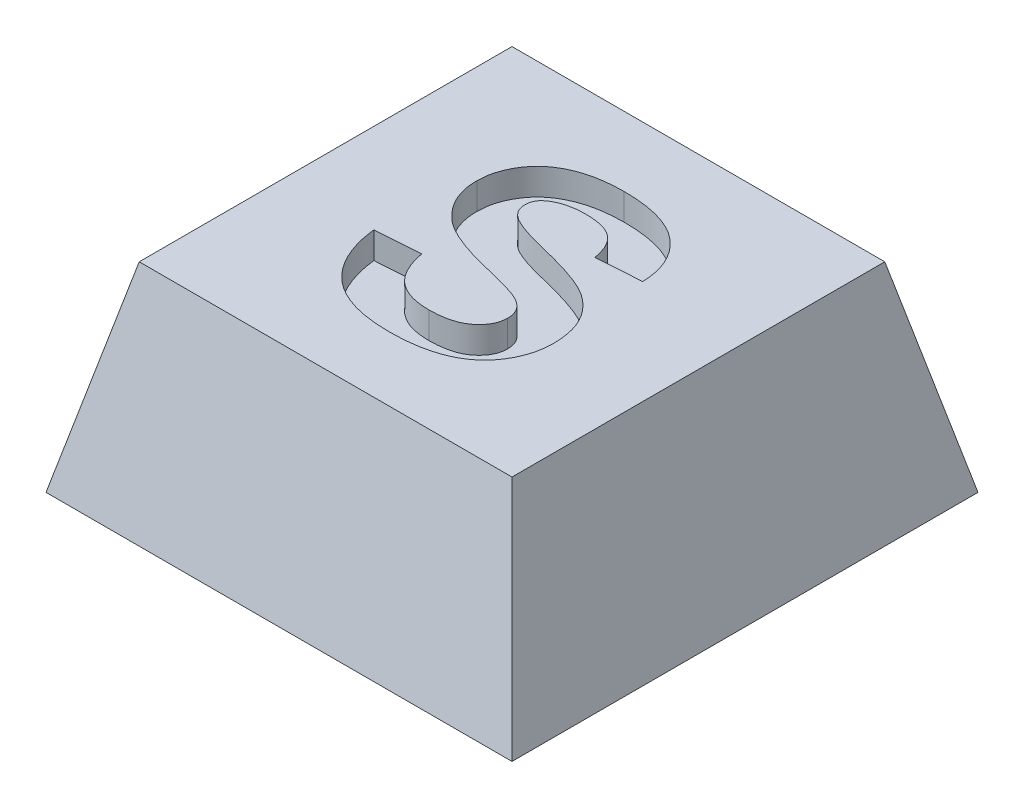
SolidWorks part; units mm, degrees
ref_plane "Front Plane" through (0, 0, 0) normal (0, 0, 1) x (1, 0, 0)
ref_plane "Top Plane" through (0, 0, 0) normal (0, 1, 0) x (1, 0, 0)
ref_plane "Right Plane" through (0, 0, 0) normal (1, 0, 0) x (0, 0, -1)
sketch "Sketch1" plane through (0, 0, 0) normal (0, 1, 0) x (1, 0, 0)
  line L1 (0, 0) -> (7, 0)
  line L2 (0, 0) -> (0, 7)
  line L3 (0, 7) -> (7, 7)
  line L4 (7, 0) -> (7, 7)
  dimension "D1" = 7
  dimension "D2" = 7
extrude "Boss-Extrude1" add sketch "Sketch1" along normal blind 3
sketch "Sketch2" plane through (0, 0, 0) normal (0, 0, 1) x (1, 0, 0)
  line L0 (0, 0) -> (0.7, 3)
  line L1 (0, 3) -> (7, 3) construction
  line L2 (0.7, 3) -> (0, 3)
  line L3 (0, 3) -> (0, 0)
  line L4 (7, 0) -> (6.3, 3)
  line L5 (6.3, 3) -> (7, 3)
  line L6 (7, 3) -> (7, 0)
  dimension "D1" = 0.7
  dimension "D2" = 0.7
extrude "Cut-Extrude1" cut sketch "Sketch2" against normal blind 7
sketch "Sketch3" plane through (0, 0, 0) normal (1, 0, 0) x (0, 0, -1)
  line L0 (0, 0) -> (0.7, 3)
  line L1 (7, 3) -> (0, 3) construction
  line L2 (0.7, 3) -> (0, 3)
  line L3 (0, 3) -> (0, 0)
  line L4 (7, 3) -> (6.3, 3)
  line L5 (6.3, 3) -> (7, 0)
  line L6 (7, 3) -> (7, 0)
  dimension "D1" = 0.7
  dimension "D2" = 0.7
extrude "Cut-Extrude2" cut sketch "Sketch3" along normal blind 11
sketch "Sketch4" plane through (0, 0, 0) normal (0, -1, 0) x (1, 0, 0)
  line L0 (3.5, 0) -> (3.5, -7) construction
  line L1 (0, 0) -> (7, 0) construction
  line L2 (7, -7) -> (0, -7) construction
  line L3 (0, -3.5) -> (7, -3.5) construction
  line L4 (0, -7) -> (0, 0) construction
  line L5 (7, 0) -> (7, -7) construction
  circle A0 centre (3.5, -3.5) radius 1.8
  dimension "D1" = 3.6
extrude "Cut-Extrude3" cut sketch "Sketch4" against normal blind 0.8
sketch "Sketch5" plane through (0, 3, 0) normal (0, 1, 0) x (1, 0, 0)
  text T0 "S" font "Arial" height 3.5
extrude "Cut-Extrude4" cut sketch "Sketch5" against normal blind 0.4
